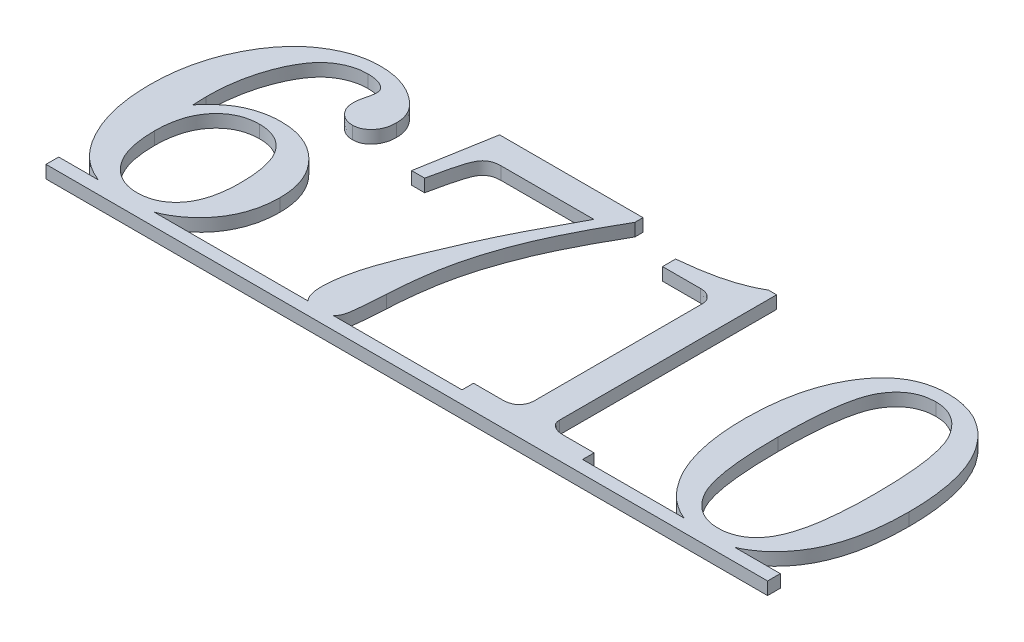
SolidWorks part; units mm, degrees
ref_plane "Front Plane" through (0, 0, 0) normal (0, 0, 1) x (1, 0, 0)
ref_plane "Top Plane" through (0, 0, 0) normal (0, 1, 0) x (1, 0, 0)
ref_plane "Right Plane" through (0, 0, 0) normal (1, 0, 0) x (0, 0, -1)
sketch "Sketch2" plane through (0, 0, 0) normal (0, 1, 0) x (1, 0, 0)
  text T0 "6710" font "Century Schoolbook" height 100
extrude "Boss-Extrude2" add sketch "Sketch2" along normal blind 5
sketch "Sketch6" plane through (0, 0, 0) normal (0, 1, 0) x (1, 0, 0)
  line L0 (-108.9311, -32.8914) -> (174.9288, -32.8914)
  line L1 (38.3231, -36.7836) -> (39.0042, -32.8914)
extrude "Extrude-Thin9" add sketch "Sketch6" along normal blind 5 thin
